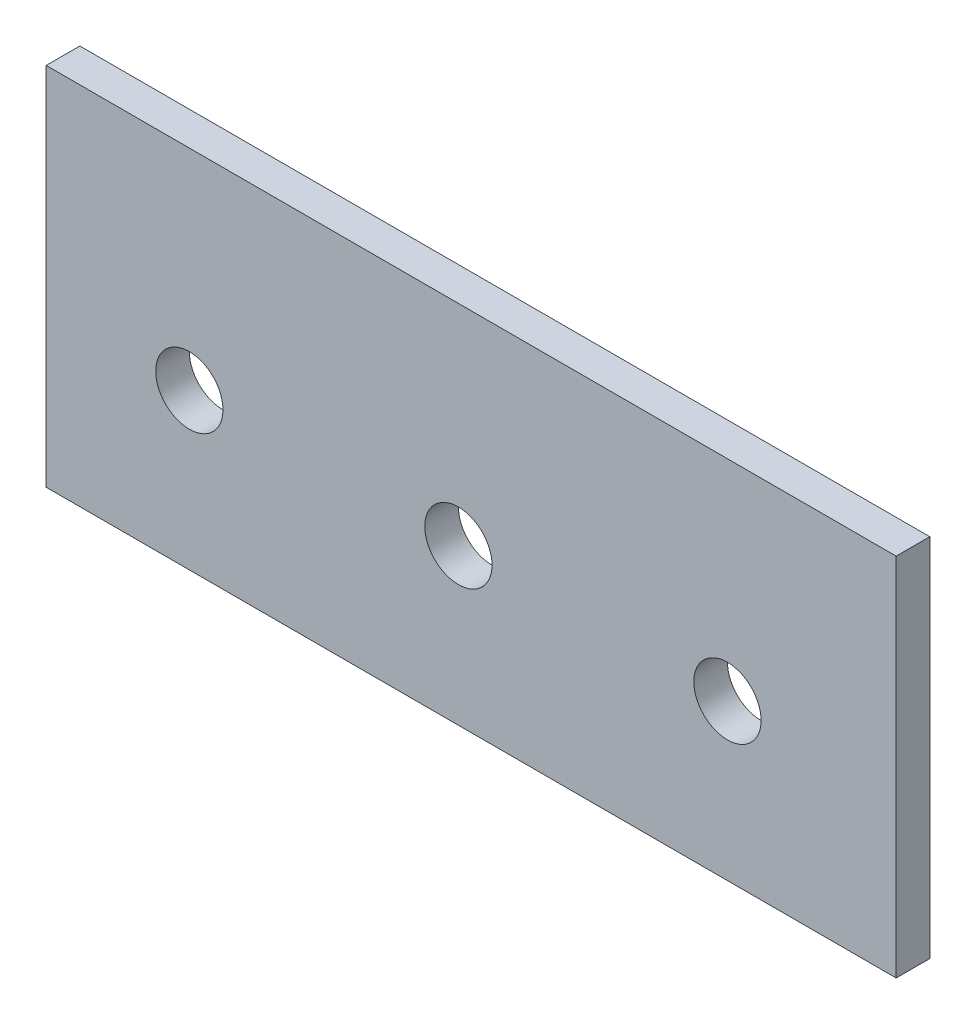
SolidWorks part; units mm, degrees
ref_plane "Front Plane" through (0, 0, 0) normal (0, 0, 1) x (1, 0, 0)
ref_plane "Top Plane" through (0, 0, 0) normal (0, 1, 0) x (1, 0, 0)
ref_plane "Right Plane" through (0, 0, 0) normal (1, 0, 0) x (0, 0, -1)
sketch "Sketch1" plane through (0, 0, 0) normal (0, 0, 1) x (1, 0, 0)
  line L1 (-89.7107, 19.8132) -> (-9.4757, 19.8132)
  line L2 (-89.7107, 19.8132) -> (-89.7107, -14.6756)
  line L3 (-89.7107, -14.6756) -> (-9.4757, -14.6756)
  line L4 (-9.4757, 19.8132) -> (-9.4757, -14.6756)
  circle A4 centre (-76.2, 0) radius 3.175
  circle A5 centre (-25.4, 0) radius 3.175
  circle A6 centre (-50.8, 0) radius 3.175
extrude "Boss-Extrude1" add sketch "Sketch1" along normal blind 3.175
